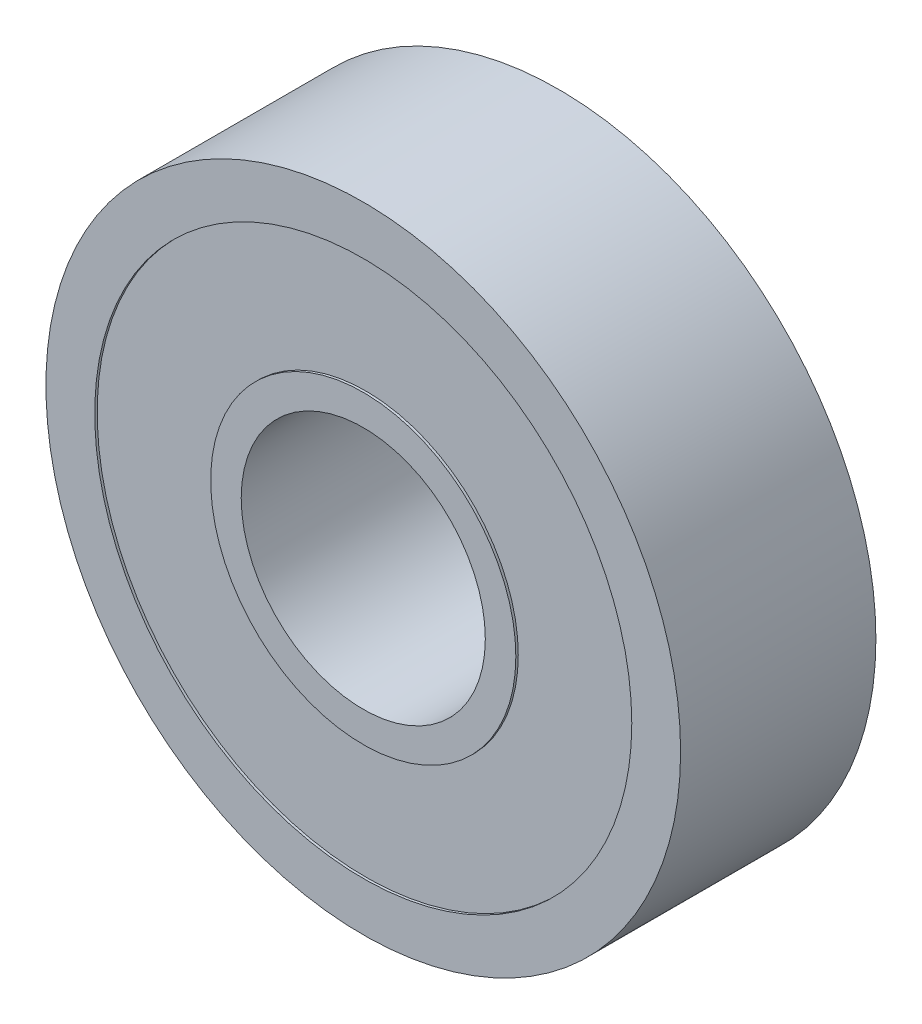
SolidWorks part; units mm, degrees
ref_plane "Alzado" through (0, 0, 0) normal (0, 0, 1) x (1, 0, 0)
ref_plane "Planta" through (0, 0, 0) normal (0, 1, 0) x (1, 0, 0)
ref_plane "Vista lateral" through (0, 0, 0) normal (1, 0, 0) x (0, 0, -1)
sketch "Croquis1" plane through (0, 0, 0) normal (0, 0, 1) x (1, 0, 0)
  circle A0 centre (0, 0) radius 5
  circle A1 centre (0, 0) radius 13
  dimension "D1" = 26
  dimension "D2" = 10
extrude "Saliente-Extruir1" add sketch "Croquis1" along normal blind 8
sketch "Croquis2" plane through (0, 0, 8) normal (0, 0, 1) x (1, 0, 0)
  circle A0 centre (0, 0) radius 6.25
  circle A1 centre (0, 0) radius 11
  dimension "12.5" = 12.5
  dimension "D2" = 22
extrude "Cortar-Extruir1" cut sketch "Croquis2" against normal blind 0.1
sketch "Croquis3" plane through (0, 0, 0) normal (0, 0, -1) x (-1, 0, 0)
  circle A0 centre (0, 0) radius 6.25
  circle A1 centre (0, 0) radius 11
  dimension "D1" = 12.5
  dimension "D2" = 22
extrude "Cortar-Extruir2" cut sketch "Croquis3" against normal blind 0.1
